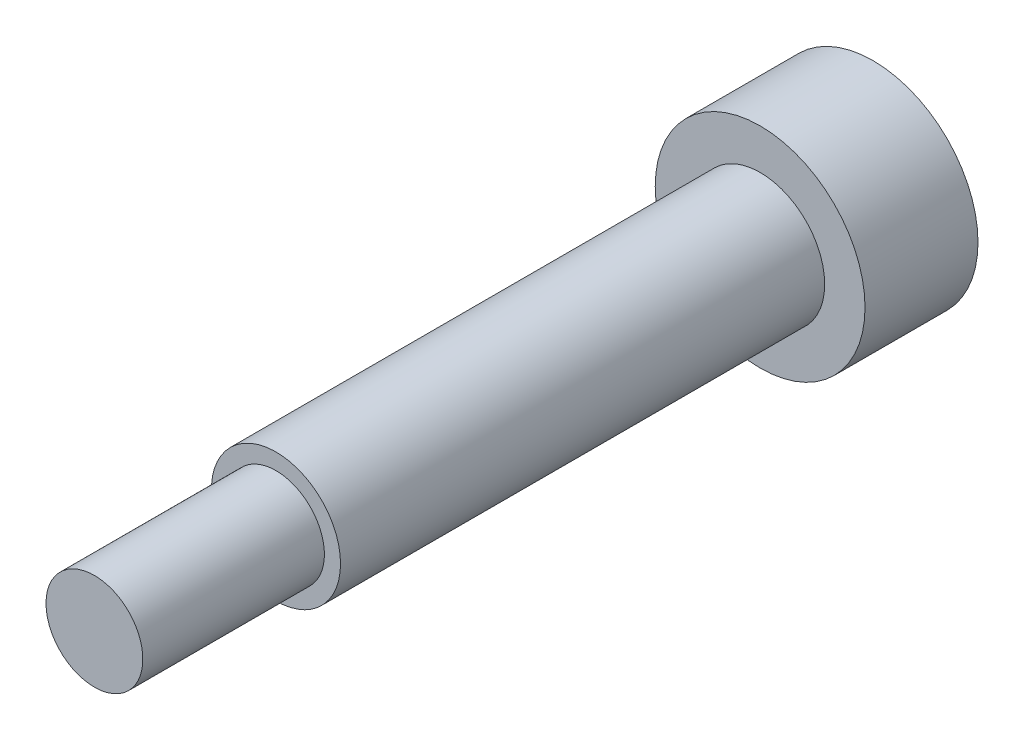
SolidWorks part; units mm, degrees
material "6061 合金"
ref_plane "前视基准面" through (0, 0, 0) normal (0, 0, 1) x (1, 0, 0)
ref_plane "上视基准面" through (0, 0, 0) normal (0, 1, 0) x (1, 0, 0)
ref_plane "右视基准面" through (0, 0, 0) normal (1, 0, 0) x (0, 0, -1)
sketch "草图1" plane through (0, 0, 0) normal (0, 0, 1) x (1, 0, 0)
  circle A0 centre (0, 0) radius 6.5
  dimension "D1" = 13
extrude "凸台-拉伸1" add sketch "草图1" along normal blind 7
sketch "草图2" plane through (0, 0, 7) normal (0, 0, 1) x (1, 0, 0)
  circle A0 centre (0, 0) radius 4
  dimension "D1" = 8
extrude "凸台-拉伸2" add sketch "草图2" along normal blind 30
sketch "草图3" plane through (0, 0, 37) normal (0, 0, 1) x (1, 0, 0)
  circle A0 centre (0, 0) radius 3
  dimension "D1" = 6
extrude "凸台-拉伸3" add sketch "草图3" along normal blind 11.25
cosmetic thread "装饰螺纹线2" parameters "D2"=5
